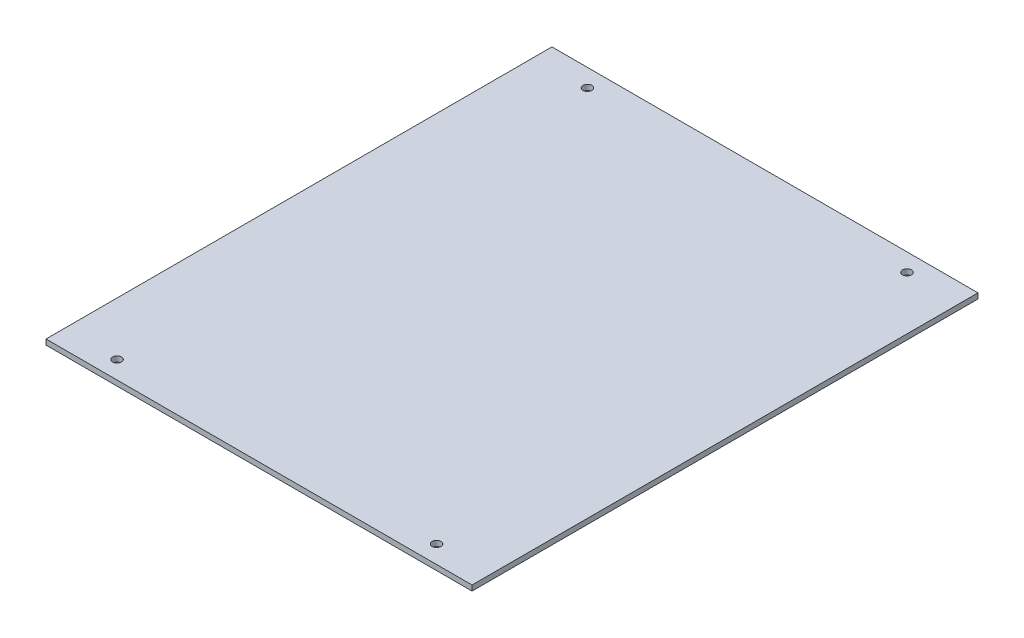
SolidWorks part; units mm, degrees
ref_plane "Front Plane" through (0, 0, 0) normal (0, 0, 1) x (1, 0, 0)
ref_plane "Top Plane" through (0, 0, 0) normal (0, 1, 0) x (1, 0, 0)
ref_plane "Right Plane" through (0, 0, 0) normal (1, 0, 0) x (0, 0, -1)
sketch "Sketch1" plane through (0, 0, 0) normal (0, 1, 0) x (1, 0, 0)
  line L1 (-120, 142.5) -> (120, 142.5)
  line L2 (-120, 142.5) -> (-120, -142.5)
  line L3 (-120, -142.5) -> (120, -142.5)
  line L4 (120, 142.5) -> (120, -142.5)
  line L5 (-120, 142.5) -> (120, -142.5) construction
  line L6 (-120, -142.5) -> (120, 142.5) construction
  point P0 (0, 0)
  dimension "D1" = 285
  dimension "D2" = 240
extrude "Boss-Extrude1" add sketch "Sketch1" along normal blind 3
sketch "Sketch2" plane through (0, 0, 0) normal (0, -1, 0) x (1, 0, 0)
  line L0 (0, 169.8713) -> (0, -185.784) construction
  line L1 (-159.6039, 0) -> (38.0875, 0) construction
  line L4 (120, 142.5) -> (120, -142.5) construction
  circle A0 centre (-90, 132.5) radius 2.5
  circle A1 centre (-90, -132.5) radius 2.5
  circle A2 centre (90, 132.5) radius 2.5
  circle A3 centre (90, -132.5) radius 2.5
  dimension "D1" = 5
  dimension "D2" = 5
  dimension "D3" = 30
  dimension "D4" = 30
extrude "Cut-Extrude1" cut sketch "Sketch2" against normal up to next
